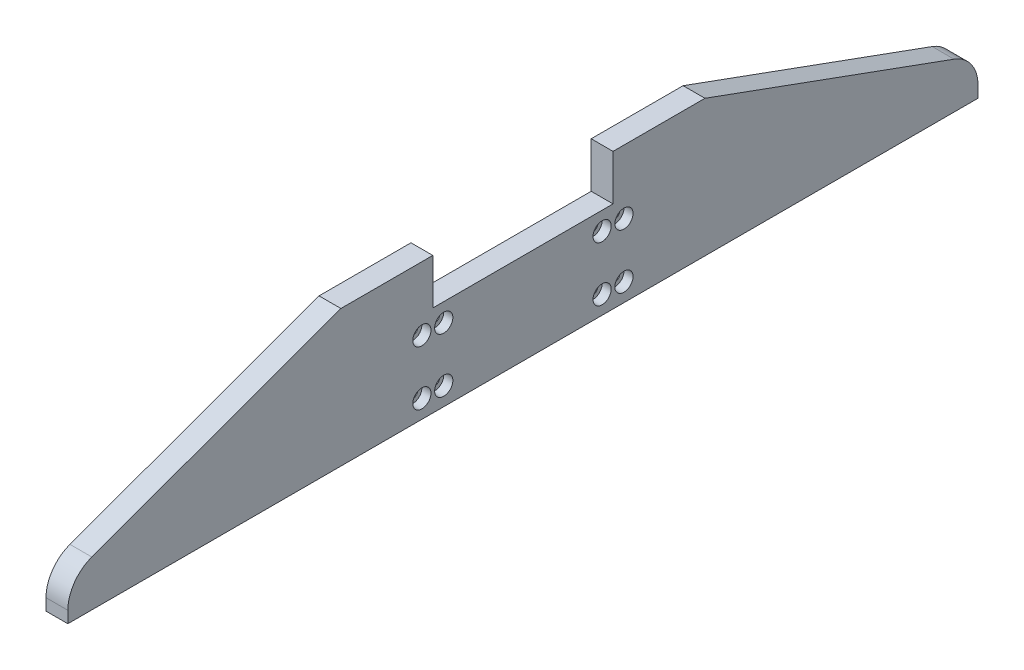
SolidWorks part; units mm, degrees
material "Beech"
ref_plane "Front Plane" through (0, 0, 0) normal (0, 0, 1) x (1, 0, 0)
ref_plane "Top Plane" through (0, 0, 0) normal (0, 1, 0) x (1, 0, 0)
ref_plane "Right Plane" through (0, 0, 0) normal (1, 0, 0) x (0, 0, -1)
sketch "Sketch1" plane through (0, 0, 0) normal (0, 0, 1) x (1, 0, 0)
  line L1 (0, 0) -> (12, 0)
  line L2 (0, 0) -> (0, 75)
  line L3 (0, 75) -> (12, 75)
  line L4 (12, 0) -> (12, 75)
  dimension "D1" = 75
  dimension "D2" = 12
extrude "base" add sketch "Sketch1" along normal blind 500
sketch "Sketch2" plane through (0, 0, 0) normal (-1, 0, 0) x (0, 0, 1)
  line L0 (250, 50) -> (250, 0) construction
  line L1 (200.5, 75) -> (299.5, 75)
  line L2 (200.5, 75) -> (200.5, 50)
  line L3 (200.5, 50) -> (299.5, 50)
  line L4 (299.5, 75) -> (299.5, 50)
  line L5 (500, 75) -> (0, 75) construction
  line L6 (500, 0) -> (0, 0) construction
  dimension "D1" = 50
  dimension "D2" = 99
extrude "lap joint cutout" cut sketch "Sketch2" against normal through all
hole_wizard "lap joint bolt hole pattern" positions "Sketch3" profile "Sketch4" counterbore size "M5" standard "ANSI Metric" end condition through all
sketch "Sketch3" plane through (12, 0, 0) normal (1, 0, 0) x (0, 0, -1)
  line L1 (-293.5, 40) -> (-206.5, 40)
  line L2 (-293.5, 40) -> (-293.5, 10)
  line L3 (-293.5, 10) -> (-206.5, 10)
  line L4 (-206.5, 40) -> (-206.5, 10)
  line L5 (-250, 40) -> (-250, 50)
  line L6 (-200.5, 50) -> (-299.5, 50) construction
  line L8 (-250, 10) -> (-250, 0)
  line L9 (-500, 0) -> (0, 0) construction
  point P1 (-293.5, 40)
  point P2 (-206.5, 10)
  point P63 (-293.5, 10)
  point P64 (-206.5, 40)
  dimension "D1" = 87
  dimension "D2" = 30
sketch "Sketch4" plane through (12, 40, 293.5) normal (0, 1, 0) x (0, 0, -1)
  line L0 (0, 0) -> (0, 12)
  line L1 (0, 12) -> (2.75, 12)
  line L3 (2.75, 12) -> (2.75, 5)
  line L4 (2.75, 5) -> (5, 5)
  line L5 (5, 5) -> (5, 0)
  line L7 (5, 0) -> (0, 0)
  line L11 (0, -6.35) -> (0, 107.95) construction
  dimension "Thru Hole Dia." = 5.5
  dimension "Thru Hole Depth" = 12
  dimension "C'Bore Dia." = 10
  dimension "C'Bore Depth" = 5
chamfer "chamfer front" distance 150 angle 20 1 edges at (6, 75, 0)
chamfer "chamfer rear" distance 150 angle 20 1 edges at (6, 75, 500)
fillet "break chamfer corners" radius 20 2 edges at (6, 20.4045, 0) (6, 20.4045, 500)
hole_wizard "cross tie bolt hole pattern" positions "Sketch7" profile "Sketch6" counterbore size "M5" standard "ANSI Metric" end condition through all
sketch "Sketch7" plane through (12, 0, 0) normal (1, 0, 0) x (0, 0, -1)
  line L1 (-311.5, 50) -> (-299.5, 50)
  line L2 (-311.5, 50) -> (-311.5, 0)
  line L3 (-311.5, 0) -> (-299.5, 0)
  line L4 (-299.5, 50) -> (-299.5, 0)
  line L5 (-500, 0) -> (0, 0) construction
  line L6 (-299.5, 50) -> (-299.5, 75) construction
  line L8 (-200.5, 50) -> (-299.5, 50) construction
  line L10 (-305.5, 50) -> (-305.5, 0)
  line L12 (-305.5, 40) -> (-311.5, 25)
  line L13 (-311.5, 25) -> (-305.5, 10)
  point P88 (-305.5, 40)
  point P90 (-305.5, 10)
  dimension "D2" = 30
  dimension "D1" = 12
sketch "Sketch6" plane through (12, 40, 305.5) normal (0, 1, 0) x (0, 0, -1)
  line L0 (0, 0) -> (0, 12)
  line L1 (0, 12) -> (2.75, 12)
  line L3 (2.75, 12) -> (2.75, 5)
  line L4 (2.75, 5) -> (5, 5)
  line L5 (5, 5) -> (5, 0)
  line L7 (5, 0) -> (0, 0)
  line L11 (0, -6.35) -> (0, 107.95) construction
  dimension "Thru Hole Dia." = 5.5
  dimension "Thru Hole Depth" = 12
  dimension "C'Bore Dia." = 10
  dimension "C'Bore Depth" = 5
ref_plane "midplane in length dimension" through (0, 0, 250) normal (0, 0, -1) x (-1, 0, 0)
mirror "mirror cross tie bolt hole pattern" about plane through (0, 0, 250) normal (0, 0, -1) of "cross tie bolt hole pattern"
equation "\"board_thickness\" = 12mm"
equation "\"way_width\"= 75mm"
equation "\"way_thickness\"= 50mm"
equation "\"radial_clearance\"= 0.1mm"
equation "\"slider_width\"= \"way_width\"-2* \"radial_clearance\""
equation "\"slider_thickness\" = \"way_thickness\" - 2 * \"radial_clearance\""
equation "\"column_width\"= \"way_width\" + 2 * \"board_thickness\""
equation "\"boxway_slot_width\" = 50mm"
equation "\"keeper_rail_width\" = (\"column_width\" - \"boxway_slot_width\")/2"
equation "\"slider_length\" = 125mm"
equation "\"nut_diameter\"= 22mm"
equation "\"nut_length\"= 15mm"
equation "\"leadscrew_diameter\"= 10mm"
equation "\"leadscrew_radial_clearance\"= 1mm"
equation "\"bearing_bolt_pattern_width\" = 35mm"
equation "\"bearing_bolt_pattern_height\" = 60mm"
equation "\"desktop_bolt_pattern_width\" = 30mm"
equation "\"desktop_bolt_pattern_height\" = 30mm"
equation "\"bearing_bolt_nut_counterbore_diameter\" = 12mm"
equation "\"bearing_bolt_nut_counterbore_depth\"= 10mm"
equation "\"desktop_depth\"= 500mm"
equation "\"desktop_width\"= 650mm"
equation "\"desktop_thickness\"= 15mm"
equation "\"leg_height\"=75mm"
equation "\"D1@Sketch1\"=\"leg_height\""
equation "\"leg_width\"=12mm"
equation "\"D2@Sketch1\"=\"leg_width\""
equation "\"leg_length\"=500mm"
equation "\"D1@base\" = \"leg_length\""
equation "\"lap_joint_height\" = 50mm"
equation "\"D1@Sketch2\"=\"lap_joint_height\""
equation "\"D2@Sketch2\"=\"column_width\""
equation "\"lap_dowel_diameter\"= 8mm"
equation "\"D1@Sketch3\"=\"column_width\"-\"board_thickness\""
equation "\"lap_dowel_hole_z_spacing\"=30"
equation "\"D2@Sketch3\"=\"lap_dowel_hole_z_spacing\""
equation "\"D1@Sketch5\"=\"board_thickness\""
equation "\"D2@Sketch5\"=\"lap_joint_height\""
equation "\"D1@Sketch7\"=\"board_thickness\""
equation "\"D2@Sketch7\"=\"lap_dowel_hole_z_spacing\""
